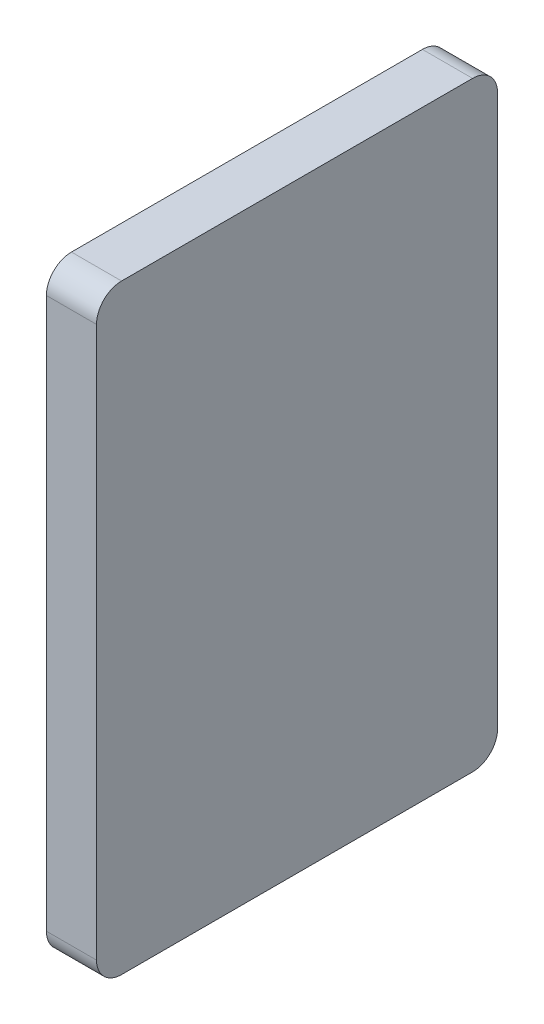
SolidWorks part; units mm, degrees
material "6061-T6 (SS)"
ref_plane "Front Plane" through (0, 0, 0) normal (0, 0, 1) x (1, 0, 0)
ref_plane "Top Plane" through (0, 0, 0) normal (0, 1, 0) x (1, 0, 0)
ref_plane "Right Plane" through (0, 0, 0) normal (1, 0, 0) x (0, 0, -1)
sketch "Sketch1" plane through (0, 0, 0) normal (1, 0, 0) x (0, 0, -1)
  line L0 (-1057.0128, 157.6046) -> (-1107.8128, 157.6046) construction
  line L1 (-1057.0128, 157.6046) -> (-1057.0128, 81.5316) construction
  line L2 (-1057.0128, 81.5316) -> (-1107.8128, 81.5316) construction
  line L3 (-1107.8128, 157.6046) -> (-1107.8128, 81.5316) construction
  line L4 (-1057.0128, 157.6046) -> (-1107.8128, 157.6046)
  line L5 (-1057.0128, 157.6046) -> (-1057.0128, 81.5316)
  line L6 (-1057.0128, 81.5316) -> (-1107.8128, 81.5316)
  line L7 (-1107.8128, 157.6046) -> (-1107.8128, 81.5316)
extrude "Boss-Extrude1" add sketch "Sketch1" along normal up to vertex (124.127 mm away) from vertex at 117.777
fillet "Fillet1" radius 3.175 4 edges at (120.952, 81.5316, 1057.0128) (120.952, 157.6046, 1107.8128) (120.952, 157.6046, 1057.0128) (120.952, 81.5316, 1107.8128)
